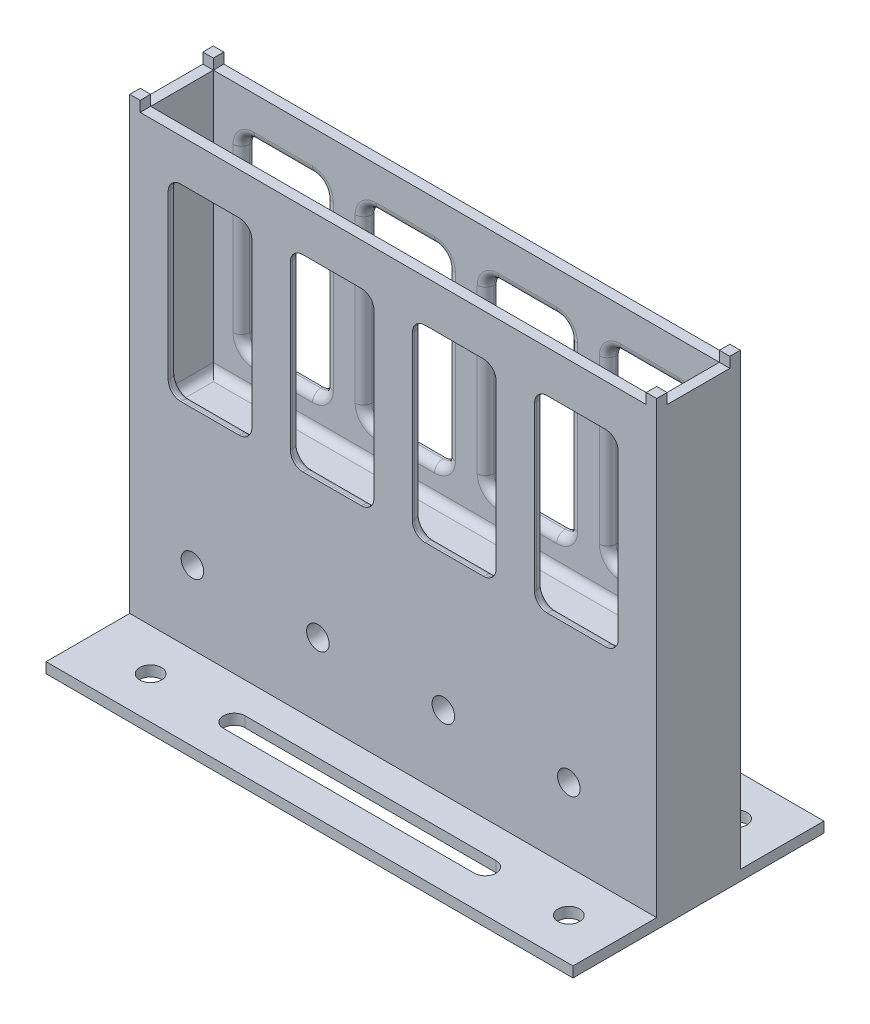
SolidWorks part; units mm, degrees
ref_plane "Front Plane" through (0, 0, 0) normal (0, 0, 1) x (1, 0, 0)
ref_plane "Top Plane" through (0, 0, 0) normal (0, 1, 0) x (1, 0, 0)
ref_plane "Right Plane" through (0, 0, 0) normal (1, 0, 0) x (0, 0, -1)
sketch "Sketch1" plane through (0, 0, 0) normal (0, 1, 0) x (1, 0, 0)
  line L1 (-80.01, -12.7) -> (80.01, -12.7)
  line L2 (-80.01, -12.7) -> (-80.01, 12.7)
  line L3 (-80.01, 12.7) -> (80.01, 12.7)
  line L4 (80.01, -12.7) -> (80.01, 12.7)
  line L5 (-80.01, -12.7) -> (80.01, 12.7) construction
  line L6 (-80.01, 12.7) -> (80.01, -12.7) construction
  point P0 (0, 0)
  dimension "D1" = 160.02
  dimension "D2" = 25.4
extrude "Boss-Extrude1" add sketch "Sketch1" along normal blind 82.55
sketch "Sketch2" plane through (0, 82.55, 0) normal (0, 1, 0) x (1, 0, 0)
  line L0 (80.01, 12.7) -> (-80.01, 12.7) construction
  line L1 (-76.835, -9.525) -> (76.835, -9.525)
  line L2 (-76.835, -9.525) -> (-76.835, 9.525)
  line L3 (-76.835, 9.525) -> (76.835, 9.525)
  line L4 (76.835, -9.525) -> (76.835, 9.525)
  line L5 (-76.835, -9.525) -> (76.835, 9.525) construction
  line L6 (-76.835, 9.525) -> (76.835, -9.525) construction
  line L7 (-80.01, 12.7) -> (-80.01, -12.7) construction
  point P0 (0, 0)
  dimension "D1" = 3.175
  dimension "D2" = 3.175
extrude "Cut-Extrude1" cut sketch "Sketch2" against normal offset from surface (79.375 mm away) 3.175 up to face at (0, 0, 0)
sketch "Sketch3" plane through (0, 0, 12.7) normal (0, 0, 1) x (1, 0, 0)
  line L0 (-80.01, 82.55) -> (-80.01, 0) construction
  line L1 (-64.516, 69.85) -> (-46.736, 69.85)
  line L2 (-68.326, 66.04) -> (-68.326, 16.51)
  line L3 (-64.516, 12.7) -> (-46.736, 12.7)
  line L4 (-42.926, 66.04) -> (-42.926, 16.51)
  line L5 (-80.01, 82.55) -> (80.01, 82.55) construction
  line L6 (-80.01, 0) -> (80.01, 0) construction
  line L7 (-27.432, 69.85) -> (-9.652, 69.85)
  line L8 (-31.242, 66.04) -> (-31.242, 16.51)
  line L9 (-27.432, 12.7) -> (-9.652, 12.7)
  line L10 (-5.842, 66.04) -> (-5.842, 16.51)
  line L11 (9.652, 69.85) -> (27.432, 69.85)
  line L12 (5.842, 66.04) -> (5.842, 16.51)
  line L13 (9.652, 12.7) -> (27.432, 12.7)
  line L14 (31.242, 66.04) -> (31.242, 16.51)
  line L15 (46.736, 69.85) -> (64.516, 69.85)
  line L16 (42.926, 66.04) -> (42.926, 16.51)
  line L17 (46.736, 12.7) -> (64.516, 12.7)
  line L18 (68.326, 66.04) -> (68.326, 16.51)
  line L47 (83.82, 69.85) -> (101.6, 69.85) [skipped]
  line L48 (80.01, 66.04) -> (80.01, 16.51) [skipped]
  line L49 (83.82, 12.7) -> (101.6, 12.7) [skipped]
  line L50 (105.41, 66.04) -> (105.41, 16.51) [skipped]
  line L51 (120.904, 69.85) -> (138.684, 69.85) [skipped]
  line L52 (117.094, 66.04) -> (117.094, 16.51) [skipped]
  line L53 (120.904, 12.7) -> (138.684, 12.7) [skipped]
  line L54 (142.494, 66.04) -> (142.494, 16.51) [skipped]
  line L55 (157.988, 69.85) -> (175.768, 69.85) [skipped]
  line L56 (154.178, 66.04) -> (154.178, 16.51) [skipped]
  line L57 (157.988, 12.7) -> (175.768, 12.7) [skipped]
  line L58 (179.578, 66.04) -> (179.578, 16.51) [skipped]
  line L59 (195.072, 69.85) -> (212.852, 69.85) [skipped]
  line L60 (191.262, 66.04) -> (191.262, 16.51) [skipped]
  line L61 (195.072, 12.7) -> (212.852, 12.7) [skipped]
  line L62 (216.662, 66.04) -> (216.662, 16.51) [skipped]
  line L63 (232.156, 69.85) -> (249.936, 69.85) [skipped]
  line L64 (228.346, 66.04) -> (228.346, 16.51) [skipped]
  line L65 (232.156, 12.7) -> (249.936, 12.7) [skipped]
  line L66 (253.746, 66.04) -> (253.746, 16.51) [skipped]
  line L67 (269.24, 69.85) -> (287.02, 69.85) [skipped]
  line L68 (265.43, 66.04) -> (265.43, 16.51) [skipped]
  line L69 (269.24, 12.7) -> (287.02, 12.7) [skipped]
  line L70 (290.83, 66.04) -> (290.83, 16.51) [skipped]
  line L71 (306.324, 69.85) -> (324.104, 69.85) [skipped]
  line L72 (302.514, 66.04) -> (302.514, 16.51) [skipped]
  line L73 (306.324, 12.7) -> (324.104, 12.7) [skipped]
  line L74 (327.914, 66.04) -> (327.914, 16.51) [skipped]
  arc A0 (-42.926, 16.51) -> (-46.736, 12.7) centre (-46.736, 16.51) cw
  arc A1 (-42.926, 66.04) -> (-46.736, 69.85) centre (-46.736, 66.04) ccw
  arc A2 (-68.326, 66.04) -> (-64.516, 69.85) centre (-64.516, 66.04) cw
  arc A3 (-68.326, 16.51) -> (-64.516, 12.7) centre (-64.516, 16.51) ccw
  arc A4 (-31.242, 66.04) -> (-27.432, 69.85) centre (-27.432, 66.04) cw
  arc A5 (-5.842, 66.04) -> (-9.652, 69.85) centre (-9.652, 66.04) ccw
  arc A6 (-31.242, 16.51) -> (-27.432, 12.7) centre (-27.432, 16.51) ccw
  arc A7 (-5.842, 16.51) -> (-9.652, 12.7) centre (-9.652, 16.51) cw
  arc A8 (5.842, 66.04) -> (9.652, 69.85) centre (9.652, 66.04) cw
  arc A9 (31.242, 66.04) -> (27.432, 69.85) centre (27.432, 66.04) ccw
  arc A10 (5.842, 16.51) -> (9.652, 12.7) centre (9.652, 16.51) ccw
  arc A11 (31.242, 16.51) -> (27.432, 12.7) centre (27.432, 16.51) cw
  arc A12 (42.926, 66.04) -> (46.736, 69.85) centre (46.736, 66.04) cw
  arc A13 (68.326, 66.04) -> (64.516, 69.85) centre (64.516, 66.04) ccw
  arc A14 (42.926, 16.51) -> (46.736, 12.7) centre (46.736, 16.51) ccw
  arc A15 (68.326, 16.51) -> (64.516, 12.7) centre (64.516, 16.51) cw
  arc A44 (80.01, 66.04) -> (83.82, 69.85) centre (83.82, 66.04) cw [skipped]
  arc A45 (105.41, 66.04) -> (101.6, 69.85) centre (101.6, 66.04) ccw [skipped]
  arc A46 (80.01, 16.51) -> (83.82, 12.7) centre (83.82, 16.51) ccw [skipped]
  arc A47 (105.41, 16.51) -> (101.6, 12.7) centre (101.6, 16.51) cw [skipped]
  arc A48 (117.094, 66.04) -> (120.904, 69.85) centre (120.904, 66.04) cw [skipped]
  arc A49 (142.494, 66.04) -> (138.684, 69.85) centre (138.684, 66.04) ccw [skipped]
  arc A50 (117.094, 16.51) -> (120.904, 12.7) centre (120.904, 16.51) ccw [skipped]
  arc A51 (142.494, 16.51) -> (138.684, 12.7) centre (138.684, 16.51) cw [skipped]
  arc A52 (154.178, 66.04) -> (157.988, 69.85) centre (157.988, 66.04) cw [skipped]
  arc A53 (179.578, 66.04) -> (175.768, 69.85) centre (175.768, 66.04) ccw [skipped]
  arc A54 (154.178, 16.51) -> (157.988, 12.7) centre (157.988, 16.51) ccw [skipped]
  arc A55 (179.578, 16.51) -> (175.768, 12.7) centre (175.768, 16.51) cw [skipped]
  arc A56 (191.262, 66.04) -> (195.072, 69.85) centre (195.072, 66.04) cw [skipped]
  arc A57 (216.662, 66.04) -> (212.852, 69.85) centre (212.852, 66.04) ccw [skipped]
  arc A58 (191.262, 16.51) -> (195.072, 12.7) centre (195.072, 16.51) ccw [skipped]
  arc A59 (216.662, 16.51) -> (212.852, 12.7) centre (212.852, 16.51) cw [skipped]
  arc A60 (228.346, 66.04) -> (232.156, 69.85) centre (232.156, 66.04) cw [skipped]
  arc A61 (253.746, 66.04) -> (249.936, 69.85) centre (249.936, 66.04) ccw [skipped]
  arc A62 (228.346, 16.51) -> (232.156, 12.7) centre (232.156, 16.51) ccw [skipped]
  arc A63 (253.746, 16.51) -> (249.936, 12.7) centre (249.936, 16.51) cw [skipped]
  arc A64 (265.43, 66.04) -> (269.24, 69.85) centre (269.24, 66.04) cw [skipped]
  arc A65 (290.83, 66.04) -> (287.02, 69.85) centre (287.02, 66.04) ccw [skipped]
  arc A66 (265.43, 16.51) -> (269.24, 12.7) centre (269.24, 16.51) ccw [skipped]
  arc A67 (290.83, 16.51) -> (287.02, 12.7) centre (287.02, 16.51) cw [skipped]
  arc A68 (302.514, 66.04) -> (306.324, 69.85) centre (306.324, 66.04) cw [skipped]
  arc A69 (327.914, 66.04) -> (324.104, 69.85) centre (324.104, 66.04) ccw [skipped]
  arc A70 (302.514, 16.51) -> (306.324, 12.7) centre (306.324, 16.51) ccw [skipped]
  arc A71 (327.914, 16.51) -> (324.104, 12.7) centre (324.104, 16.51) cw [skipped]
  point P54 (-42.926, 69.85)
  point P57 (-68.326, 69.85)
  dimension "D7" = 3.81
  dimension "D1" = 11.684
  dimension "D2" = 25.4
  dimension "D3" = 12.7
  dimension "D4" = 12.7
  dimension "D6" = 11.684
  dimension "D5" = 11
extrude "Cut-Extrude2" cut sketch "Sketch3" against normal through all
sketch "Sketch5" plane through (0, 82.55, 0) normal (0, 1, 0) x (1, 0, 0)
  line L0 (80.01, 12.7) -> (-80.01, 12.7) construction
  line L1 (-80.01, 12.7) -> (-76.835, 12.7)
  line L2 (-80.01, 12.7) -> (-80.01, 9.525)
  line L3 (-80.01, 9.525) -> (-76.835, 9.525)
  line L4 (-76.835, 12.7) -> (-76.835, 9.525)
  line L5 (-80.01, 12.7) -> (-80.01, -12.7) construction
  line L6 (-76.835, 9.525) -> (-76.835, -9.525) construction
  line L7 (76.835, 9.525) -> (-76.835, 9.525) construction
  line L8 (-76.835, -9.525) -> (76.835, -9.525) construction
  line L9 (-80.01, -12.7) -> (-76.835, -12.7)
  line L10 (-80.01, -12.7) -> (-80.01, -9.525)
  line L11 (-80.01, -9.525) -> (-76.835, -9.525)
  line L12 (-76.835, -12.7) -> (-76.835, -9.525)
  line L13 (76.835, -12.7) -> (80.01, -12.7)
  line L14 (76.835, -12.7) -> (76.835, -9.525)
  line L15 (76.835, -9.525) -> (80.01, -9.525)
  line L16 (80.01, -12.7) -> (80.01, -9.525)
  line L17 (80.01, 12.7) -> (76.835, 12.7)
  line L18 (80.01, 12.7) -> (80.01, 9.525)
  line L19 (80.01, 9.525) -> (76.835, 9.525)
  line L20 (76.835, 12.7) -> (76.835, 9.525)
  line L21 (-76.835, 9.525) -> (-76.835, -9.525) construction
  line L22 (-80.01, -12.7) -> (80.01, -12.7) construction
  line L23 (80.01, -12.7) -> (80.01, 12.7) construction
  line L24 (-76.835, -9.525) -> (76.835, -9.525) construction
  line L25 (76.835, -9.525) -> (76.835, 9.525) construction
extrude "Boss-Extrude2" add sketch "Sketch5" along normal blind 3.175
sketch "Sketch6" plane through (0, 0, 0) normal (0, -1, 0) x (1, 0, 0)
  line L0 (-80.01, 12.7) -> (80.01, 12.7) construction
  line L1 (-80.01, 12.7) -> (80.01, 12.7)
  line L2 (-80.01, 12.7) -> (-80.01, -12.7)
  line L3 (-80.01, -12.7) -> (80.01, -12.7)
  line L4 (80.01, 12.7) -> (80.01, -12.7)
  line L5 (80.01, -12.7) -> (-80.01, -12.7) construction
  line L6 (-80.01, -12.7) -> (-80.01, 12.7) construction
  line L7 (80.01, 12.7) -> (80.01, -12.7) construction
extrude "Boss-Extrude3" add sketch "Sketch6" along normal blind 50.8
sketch "Sketch7" plane through (0, -50.8, 0) normal (0, -1, 0) x (-1, 0, 0)
  line L0 (80.01, -12.7) -> (80.01, 12.7) construction
  line L1 (-80.01, 38.1) -> (80.01, 38.1)
  line L2 (-80.01, 38.1) -> (-80.01, -38.1)
  line L3 (-80.01, -38.1) -> (80.01, -38.1)
  line L4 (80.01, 38.1) -> (80.01, -38.1)
  line L5 (-80.01, 38.1) -> (80.01, -38.1) construction
  line L6 (-80.01, -38.1) -> (80.01, 38.1) construction
  point P0 (0, 0)
  dimension "D1" = 76.2
extrude "Boss-Extrude4" add sketch "Sketch7" along normal blind 3.175
sketch "Sketch8" plane through (0, -50.8, 0) normal (0, 1, 0) x (1, 0, 0)
  line L0 (-80.01, 38.1) -> (80.01, 38.1) construction
  line L1 (-80.01, -38.1) -> (-80.01, -12.7) construction
  line L2 (-35.56, 28.702) -> (40.64, 28.702)
  line L3 (-35.56, 22.098) -> (40.64, 22.098)
  line L4 (-35.56, -22.098) -> (40.64, -22.098)
  line L5 (-35.56, -28.702) -> (40.64, -28.702)
  circle A0 centre (-60.96, 25.4) radius 3.302
  arc A1 (-35.56, 28.702) -> (-35.56, 22.098) centre (-35.56, 25.4) ccw
  arc A4 (40.64, 22.098) -> (40.64, 28.702) centre (40.64, 25.4) ccw
  circle A5 centre (66.04, 25.4) radius 3.302
  arc A8 (-35.56, -22.098) -> (-35.56, -28.702) centre (-35.56, -25.4) ccw
  arc A11 (40.64, -28.702) -> (40.64, -22.098) centre (40.64, -25.4) ccw
  circle A12 centre (66.04, -25.4) radius 3.302
  circle A15 centre (-60.96, -25.4) radius 3.302
  dimension "D1" = 6.604
  dimension "D2" = 12.7
  dimension "D3" = 19.05
  dimension "D6" = 76.2
  dimension "D4" = 25.4
  dimension "D5" = 127
  dimension "D7" = 50.8
extrude "Cut-Extrude3" cut sketch "Sketch8" against normal through all
fillet "Fillet1" radius 2.54 64 edges at (-6.9579, 68.7341, -9.525) (-18.542, 69.85, -9.525) (-30.1261, 68.7341, -9.525) (-31.242, 41.275, -9.525) (-30.1261, 13.8159, -9.525) (-18.542, 12.7, -9.525) (-6.9579, 13.8159, -9.525) (-5.842, 41.275, -9.525) (-44.0419, 68.7341, -9.525) (-55.626, 69.85, -9.525) (-67.2101, 68.7341, -9.525) (-68.326, 41.275, -9.525) (-67.2101, 13.8159, -9.525) (-55.626, 12.7, -9.525) (-44.0419, 13.8159, -9.525) (-42.926, 41.275, -9.525) (67.2101, 68.7341, -9.525) (55.626, 69.85, -9.525) (44.0419, 68.7341, -9.525) (42.926, 41.275, -9.525) (44.0419, 13.8159, -9.525) (55.626, 12.7, -9.525) (67.2101, 13.8159, -9.525) (68.326, 41.275, -9.525) (30.1261, 68.7341, -9.525) (18.542, 69.85, -9.525) (6.9579, 68.7341, -9.525) (5.842, 41.275, -9.525) (6.9579, 13.8159, -9.525) (18.542, 12.7, -9.525) (30.1261, 13.8159, -9.525) (31.242, 41.275, -9.525) (-67.2101, 13.8159, 9.525) (-68.326, 41.275, 9.525) (-67.2101, 68.7341, 9.525) (-55.626, 69.85, 9.525) (-44.0419, 68.7341, 9.525) (-42.926, 41.275, 9.525) (-44.0419, 13.8159, 9.525) (-55.626, 12.7, 9.525) (-30.1261, 13.8159, 9.525) (-31.242, 41.275, 9.525) (-30.1261, 68.7341, 9.525) (-18.542, 69.85, 9.525) (-6.9579, 68.7341, 9.525) (-5.842, 41.275, 9.525) (-6.9579, 13.8159, 9.525) (-18.542, 12.7, 9.525) (6.9579, 13.8159, 9.525) (5.842, 41.275, 9.525) (6.9579, 68.7341, 9.525) (18.542, 69.85, 9.525) (30.1261, 68.7341, 9.525) (31.242, 41.275, 9.525) (30.1261, 13.8159, 9.525) (18.542, 12.7, 9.525) (44.0419, 13.8159, 9.525) (42.926, 41.275, 9.525) (44.0419, 68.7341, 9.525) (55.626, 69.85, 9.525) (67.2101, 68.7341, 9.525) (68.326, 41.275, 9.525) (67.2101, 13.8159, 9.525) (55.626, 12.7, 9.525)
ref_plane "Plane1" through (0, -28.575, 0) normal (0, 1, 0) x (1, 0, 0)
sketch "Sketch9" plane through (0, 0, 0) normal (0, 0, 1) x (1, 0, 0)
  line L0 (-66.421, -31.7279) -> (-66.421, -65.5405)
  line L1 (-66.421, -31.7279) -> (-60.96, -34.8808) construction
  line L2 (-60.96, -34.8808) -> (-55.499, -31.7279) construction
  line L3 (-55.499, -31.7279) -> (-55.499, -25.4221)
  line L4 (-55.499, -25.4221) -> (-60.96, -22.2692)
  line L5 (-60.96, -22.2692) -> (-66.421, -25.4221)
  line L6 (-66.421, -25.4221) -> (-66.421, -31.7279)
  line L7 (-66.421, -65.5405) -> (-55.499, -65.5405)
  line L8 (-55.499, -65.5405) -> (-55.499, -31.7279)
  line L9 (-80.01, 85.725) -> (-80.01, -50.8) construction
  line L10 (-28.321, -65.5405) -> (-17.399, -65.5405)
  line L11 (41.91, -28.575) -> (-41.91, -28.575) construction
  line L12 (-17.399, -65.5405) -> (-17.399, -31.7279)
  line L13 (-17.399, -31.7279) -> (-17.399, -25.4221)
  line L14 (-17.399, -25.4221) -> (-22.86, -22.2692)
  line L15 (-22.86, -22.2692) -> (-28.321, -25.4221)
  line L16 (-28.321, -25.4221) -> (-28.321, -31.7279)
  line L17 (-28.321, -31.7279) -> (-28.321, -65.5405)
  line L18 (9.779, -65.5405) -> (20.701, -65.5405)
  line L19 (20.701, -65.5405) -> (20.701, -31.7279)
  line L20 (20.701, -31.7279) -> (20.701, -25.4221)
  line L21 (20.701, -25.4221) -> (15.24, -22.2692)
  line L22 (15.24, -22.2692) -> (9.779, -25.4221)
  line L23 (9.779, -25.4221) -> (9.779, -31.7279)
  line L24 (9.779, -31.7279) -> (9.779, -65.5405)
  line L25 (47.879, -65.5405) -> (58.801, -65.5405)
  line L26 (58.801, -65.5405) -> (58.801, -31.7279)
  line L27 (58.801, -31.7279) -> (58.801, -25.4221)
  line L28 (58.801, -25.4221) -> (53.34, -22.2692)
  line L29 (53.34, -22.2692) -> (47.879, -25.4221)
  line L30 (47.879, -25.4221) -> (47.879, -31.7279)
  line L31 (47.879, -31.7279) -> (47.879, -65.5405)
  circle A0 centre (-60.96, -28.575) radius 5.461 construction
  dimension "D1" = 10.922
  dimension "D2" = 19.05
  dimension "D3" = 4
  dimension "D4" = 38.1
extrude "Cut-Extrude4" cut sketch "Sketch9" against normal mid plane 5.842
sketch "Sketch10" plane through (0, 0, 0) normal (0, 0, 1) x (1, 0, 0)
  line L0 (41.91, -28.575) -> (-41.91, -28.575) construction
  line L1 (-80.01, 85.725) -> (-80.01, -50.8) construction
  circle A0 centre (-60.96, -28.575) radius 3.429
  circle A1 centre (-22.86, -28.575) radius 3.429
  circle A2 centre (15.24, -28.575) radius 3.429
  circle A3 centre (53.34, -28.575) radius 3.429
  dimension "D1" = 6.858
  dimension "D2" = 19.05
extrude "Cut-Extrude5" cut sketch "Sketch10" against normal through all both and the other way through all
fillet "Fillet2" radius 2.54 4 edges at (-76.835, 3.175, 0) (0, 3.175, 9.525) (76.835, 3.175, 0) (0, 3.175, -9.525)
